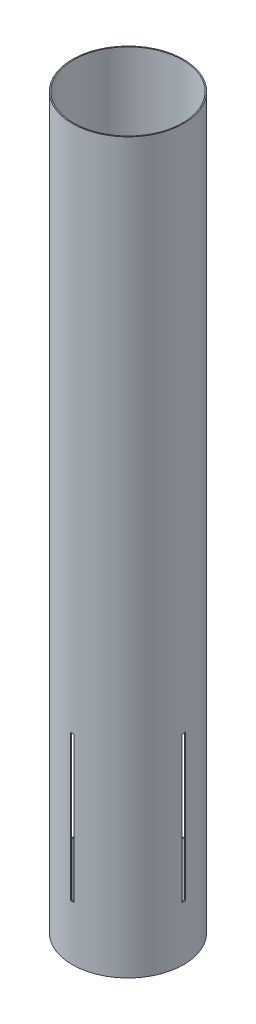
SolidWorks part; units mm, degrees
material "Thornel Mat VMA"
ref_plane "Front Plane" through (0, 0, 0) normal (0, 0, 1) x (1, 0, 0)
ref_plane "Top Plane" through (0, 0, 0) normal (0, 1, 0) x (1, 0, 0)
ref_plane "Right Plane" through (0, 0, 0) normal (1, 0, 0) x (0, 0, -1)
sketch "Sketch1" plane through (0, 0, 0) normal (0, 1, 0) x (1, 0, 0)
  circle A0 centre (0, 0) radius 77.6224
  circle A1 centre (0, 0) radius 76.2
  dimension "D1" = 155.2448
  dimension "D2" = 152.4
extrude "Boss-Extrude1" add sketch "Sketch1" along normal mid plane 1016
sketch "Sketch3" plane through (0, 0, 0) normal (0, 0, 1) x (1, 0, 0)
  line L0 (0, 508) -> (0, -508) construction
  line L1 (-2.3749, -431.8) -> (2.3749, -431.8)
  line L2 (-2.3749, -431.8) -> (-2.3749, -228.6)
  line L3 (-2.3749, -228.6) -> (2.3749, -228.6)
  line L4 (2.3749, -431.8) -> (2.3749, -228.6)
  line L5 (-2.3749, -431.8) -> (2.3749, -228.6) construction
  line L6 (-2.3749, -228.6) -> (2.3749, -431.8) construction
  line L7 (-77.6224, -508) -> (77.6224, -508) construction
  point P0 (0, -330.2)
  dimension "D1" = 4.7498
  dimension "D2" = 0
  dimension "D3" = 203.2
  dimension "D4" = 76.2
extrude "Cut-Extrude1" cut sketch "Sketch3" against normal through all
pattern_circular "CirPattern2" count 4 over 360 about axis through (0, 0, 0) along (0, 1, 0) of "Cut-Extrude1"
equation "\"airframeInnerDiameter\"= 6in"
equation "\"outerDiameter\"= 6.112in"
equation "\"airframeBulkheadThickness\"= 0.125in"
equation "\"payloadAirframeLength\"= 10in"
equation "\"payloadInnerDiameter\"= 6in - 0.056in"
equation "\"payloadOuterDiameter\"= \"airframeInnerDiameter\""
equation "\"payloadLength\"= 11in"
equation "\"payloadBand\"= 2in"
equation "\"payloadOffsetFromAft\"= 6in"
equation "\"upperAirframeLength\"= 25in"
equation "\"recoveryBayInnerDiameter\"= 5.888in"
equation "\"recoveryLength\"= 8in"
equation "\"recoveryBand\"= 2in"
equation "\"recoveryCouplerOuter\"=\"airframeInnerDiameter\""
equation "\"recoveryOffsetFromAft\"= 3in"
equation "\"midAirframeLength\"= 20in"
equation "\"atsLength\"= 11in"
equation "\"atsInner\"= 5.888in"
equation "\"atsBand\"= 2in"
equation "\"atsCouplerOuter\"=\"airframeInnerDiameter\""
equation "\"atsOffsetFromAft\"= 3in"
equation "\"lowerAirframeLength\"= 40in"
equation "\"finSlotLength\"= 8in"
equation "\"finSlotOffsetFromAft\"= 3in"
equation "\"finSlotWidth\"= 0.187in"
equation "\"D1@Sketch1\"=\"outerDiameter\""
equation "\"D2@Sketch1\"=\"airframeInnerDiameter\""
equation "\"D1@Boss-Extrude1\"=\"lowerAirframeLength\""
equation "\"D1@Sketch3\"=\"finSlotWidth\""
equation "\"D3@Sketch3\"=\"finSlotLength\""
equation "\"D4@Sketch3\"=\"finSlotOffsetFromAft\""
